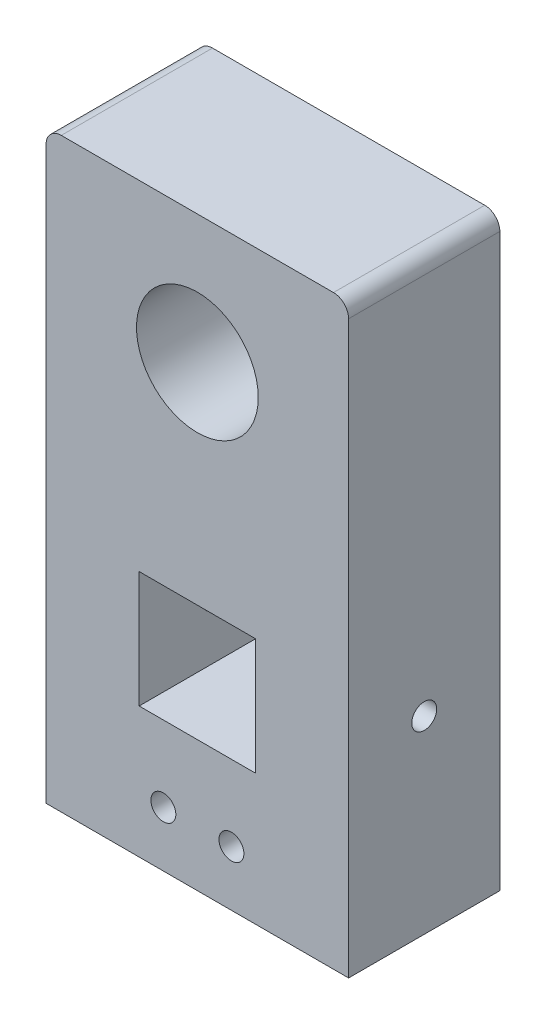
SolidWorks part; units mm, degrees
ref_plane "前视基准面" through (0, 0, 0) normal (0, 0, 1) x (1, 0, 0)
ref_plane "上视基准面" through (0, 0, 0) normal (0, 1, 0) x (1, 0, 0)
ref_plane "右视基准面" through (0, 0, 0) normal (1, 0, 0) x (0, 0, -1)
sketch "草图1" plane through (0, 0, 0) normal (0, 0, 1) x (1, 0, 0)
  line L1 (-20, -27.5) -> (20, -27.5)
  line L2 (-20, -27.5) -> (-20, 27.5)
  line L3 (-20, 27.5) -> (20, 27.5)
  line L4 (20, -27.5) -> (20, 27.5)
  line L5 (-20, -27.5) -> (20, 27.5) construction
  line L6 (-20, 27.5) -> (20, -27.5) construction
  point P0 (0, 0)
  dimension "D1" = 40
  dimension "D2" = 55
extrude "凸台-拉伸1" add sketch "草图1" along normal blind 20
sketch "草图2" plane through (0, 0, 20) normal (0, 0, 1) x (1, 0, 0)
  circle A1 centre (0, 10.5) radius 8.05
  dimension "D1" = 16.1
  dimension "D2" = 10.5
extrude "切除-拉伸1" cut sketch "草图2" against normal blind 20
sketch "草图3" plane through (0, -27.5, 0) normal (0, -1, 0) x (1, 0, 0)
  line L1 (-20, 0) -> (20, 0)
  line L2 (-20, 0) -> (-20, 20)
  line L3 (-20, 20) -> (20, 20)
  line L4 (20, 0) -> (20, 20)
  line L5 (-20, 0) -> (20, 20) construction
  line L6 (-20, 20) -> (20, 0) construction
  point P0 (0, 10)
extrude "凸台-拉伸2" add sketch "草图3" along normal blind 32.5
sketch "草图6" plane through (0, 0, 20) normal (0, 0, 1) x (1, 0, 0)
  line L0 (0, -5.8335) -> (0, -63.4582) construction
  line L1 (20, -60) -> (-20, -60) construction
  line L2 (-7.7, -32.7) -> (7.7, -32.7)
  line L3 (-7.7, -32.7) -> (-7.7, -17.3)
  line L4 (-7.7, -17.3) -> (7.7, -17.3)
  line L5 (7.7, -32.7) -> (7.7, -17.3)
  line L6 (-7.7, -32.7) -> (7.7, -17.3) construction
  line L7 (-7.7, -17.3) -> (7.7, -32.7) construction
  point P3 (0, -25)
  dimension "D1" = 15.4
  dimension "D2" = 15.4
  dimension "D3" = 35
extrude "切除-拉伸4" cut sketch "草图6" against normal blind 1000
sketch "草图4" plane through (0, 0, 20) normal (0, 0, 1) x (1, 0, 0)
  line L1 (-7.7, -32.7) -> (7.7, -32.7) construction
  line L2 (0, 24.4829) -> (0, -73.983) construction
  circle A0 centre (4.5, -42.7) radius 1.65
  circle A1 centre (-4.5, -42.7) radius 1.65
  dimension "D1" = 3.3
  dimension "D2" = 10
  dimension "D3" = 3.3
  dimension "D4" = 4.5
  dimension "D5" = 4.5
  dimension "D6" = 10
extrude "切除-拉伸2" cut sketch "草图4" against normal blind 40
sketch "草图5" plane through (0, -60, 0) normal (0, -1, 0) x (1, 0, 0)
  line L0 (0, 21.447) -> (0, -4.8794) construction
  line L2 (-2.5, 9.5) -> (2.5, 9.5)
  line L3 (-2.5, 9.5) -> (-2.5, 14.5)
  line L4 (-2.5, 14.5) -> (2.5, 14.5)
  line L5 (2.5, 9.5) -> (2.5, 14.5)
  line L6 (-2.5, 9.5) -> (2.5, 14.5) construction
  line L7 (-2.5, 14.5) -> (2.5, 9.5) construction
  line L9 (20, 20) -> (-20, 20) construction
  point P3 (0, 12)
  dimension "D1" = 5
  dimension "D2" = 5
  dimension "D3" = 8
extrude "切除-拉伸3" cut sketch "草图5" against normal blind 6
fillet "圆角1" radius 2 2 edges at (20, 27.5, 10) (-20, 27.5, 10)
sketch "草图7" plane through (0, 0, 20) normal (0, 0, 1) x (1, 0, 0)
  line L0 (0, 9.6884) -> (0, -67.547) construction
  line L1 (20, -60) -> (-20, -60) construction
  line L2 (-23.782, -61.4632) -> (23.782, -61.4632)
  line L3 (-23.782, -61.4632) -> (-23.782, -50)
  line L4 (-23.782, -50) -> (23.782, -50)
  line L5 (23.782, -61.4632) -> (23.782, -50)
  line L6 (-23.782, -61.4632) -> (23.782, -50) construction
  line L7 (-23.782, -50) -> (23.782, -61.4632) construction
  point P3 (0, -55.7316)
  dimension "D1" = 10
extrude "切除-拉伸5" cut sketch "草图7" against normal blind 100
sketch "草图8" plane through (20, 0, 0) normal (1, 0, 0) x (0, 0, -1)
  line L0 (-10, -50) -> (-10, 4.5212) construction
  line L2 (-20, -50) -> (0, -50) construction
  circle A0 centre (-10, -25) radius 1.65
  dimension "D1" = 3.3
  dimension "D2" = 25
extrude "切除-拉伸6" cut sketch "草图8" against normal blind 1000
sketch "草图9" plane through (0, -50, 0) normal (0, -1, 0) x (1, 0, 0)
  line L4 (20, 20) -> (-20, 20)
  line L5 (-20, 20) -> (-20, 0)
  line L6 (-20, 0) -> (20, 0)
  line L7 (20, 0) -> (20, 20)
  line L8 (20, 20) -> (-20, 20)
  line L9 (-20, 20) -> (-20, 0)
  line L10 (-20, 0) -> (20, 0)
  line L11 (20, 0) -> (20, 20)
  dimension "D1" = 0
extrude "凸台-拉伸3" [suppressed] add sketch "草图9" along normal blind 60
sketch "草图10" [suppressed] plane through (0, 0, 20) normal (0, 0, 1) x (1, 0, 0)
  line L0 (0, 0) -> (0, -157.1196) construction
  line L2 (-10.2, -97.75) -> (10.2, -97.75)
  line L3 (-10.2, -97.75) -> (-10.2, -77.35)
  line L4 (-10.2, -77.35) -> (10.2, -77.35)
  line L5 (10.2, -97.75) -> (10.2, -77.35)
  line L6 (-10.2, -97.75) -> (10.2, -77.35) construction
  line L7 (-10.2, -77.35) -> (10.2, -97.75) construction
  line L9 (20, -110) -> (-20, -110) construction
  point P3 (0, -87.55)
  dimension "D1" = 20.4
  dimension "D2" = 20.4
  dimension "D3" = 12.25
extrude "切除-拉伸7" [suppressed] cut sketch "草图10" against normal blind 60
sketch "草图11" [suppressed] plane through (0, 0, 20) normal (0, 0, 1) x (1, 0, 0)
  line L0 (-33.0633, -67.35) -> (42.7435, -67.35) construction
  line L1 (0, -53.633) -> (0, -116.7425) construction
  line L2 (10.2, -77.35) -> (-10.2, -77.35) construction
  circle A0 centre (4.5, -67.35) radius 1.65
  circle A1 centre (-4.5, -67.35) radius 1.65
  dimension "D2" = 9
  dimension "D3" = 4.5
  dimension "D4" = 3.3
  dimension "D5" = 3.3
  dimension "D1" = 10
extrude "切除-拉伸8" [suppressed] cut sketch "草图11" against normal blind 60
sketch "草图12" [suppressed] plane through (20, 0, 0) normal (1, 0, 0) x (0, 0, -1)
  line L0 (-10, 25.5) -> (-10, -110) construction
  line L1 (0, 25.5) -> (-20, 25.5) construction
  line L2 (0, -110) -> (-20, -110) construction
  circle A1 centre (-10, -87.55) radius 1.65
  dimension "D1" = 3.3
  dimension "D2" = 22.45
extrude "切除-拉伸9" [suppressed] cut sketch "草图12" against normal blind 60
